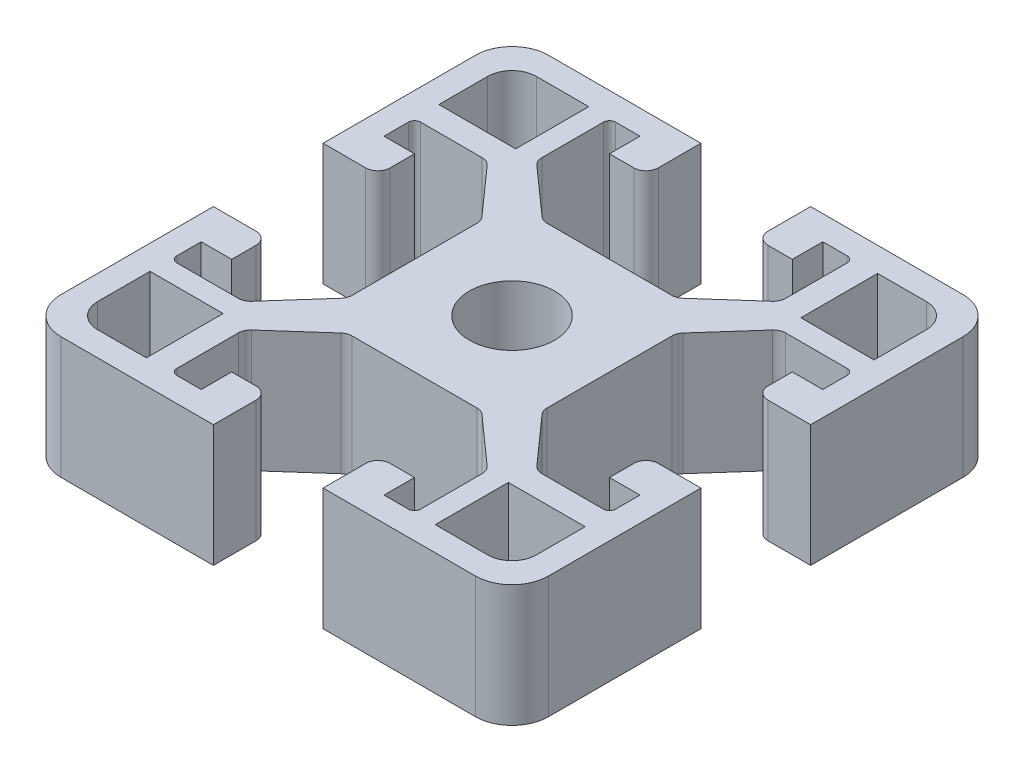
SolidWorks part; units mm, degrees
ref_plane "前视基准面" through (0, 0, 0) normal (0, 0, 1) x (1, 0, 0)
ref_plane "上视基准面" through (0, 0, 0) normal (0, 1, 0) x (1, 0, 0)
ref_plane "右视基准面" through (0, 0, 0) normal (1, 0, 0) x (0, 0, -1)
sketch "草图1" plane through (0, 0, 0) normal (0, 1, 0) x (1, 0, 0)
  line L0 (0, 32.6515) -> (0, -47.5) construction
  line L1 (11.7017, 9.6644) -> (8.2526, 5.7842)
  line L2 (-54.5455, 0) -> (57.7273, 0) construction
  line L3 (-17, 20) -> (-4.5, 20)
  line L4 (-20, 17) -> (-20, 4.5)
  line L5 (-17, -20) -> (-4.5, -20)
  line L6 (20, 17) -> (20, 4.5)
  line L7 (-9.6644, 11.7017) -> (-5.7842, 8.2526)
  line L8 (-10, 17.5) -> (-10, 12.4491)
  line L9 (-7.5, 18) -> (-9.5, 18)
  line L10 (-7.5, 15.5) -> (-7.5, 18)
  line L11 (-5.5, 15.5) -> (-7.5, 15.5)
  line L12 (-4.5, 20) -> (-4.5, 16.5)
  line L14 (17.5, 10) -> (12.4491, 10)
  line L15 (18, 7.5) -> (18, 9.5)
  line L16 (15.5, 7.5) -> (18, 7.5)
  line L17 (15.5, 5.5) -> (15.5, 7.5)
  line L18 (20, 4.5) -> (16.5, 4.5)
  line L20 (20, -4.5) -> (16.5, -4.5)
  line L21 (15.5, -5.5) -> (15.5, -7.5)
  line L22 (15.5, -7.5) -> (18, -7.5)
  line L23 (4.5, 20) -> (4.5, 16.5)
  line L24 (5.5, 15.5) -> (7.5, 15.5)
  line L25 (7.5, 15.5) -> (7.5, 18)
  line L26 (7.5, 18) -> (9.5, 18)
  line L27 (10, 17.5) -> (10, 12.4491)
  line L28 (9.6644, 11.7017) -> (5.7842, 8.2526)
  line L29 (5.1198, 8) -> (-5.1198, 8)
  line L30 (18, -7.5) -> (18, -9.5)
  line L31 (17.5, -10) -> (12.4491, -10)
  line L32 (11.7017, -9.6644) -> (8.2526, -5.7842)
  line L33 (8, -5.1198) -> (8, 5.1198)
  line L34 (9.6644, -11.7017) -> (5.7842, -8.2526)
  line L35 (10, -17.5) -> (10, -12.4491)
  line L36 (7.5, -18) -> (9.5, -18)
  line L37 (7.5, -15.5) -> (7.5, -18)
  line L38 (5.5, -15.5) -> (7.5, -15.5)
  line L39 (4.5, -20) -> (4.5, -16.5)
  line L41 (-4.5, -20) -> (-4.5, -16.5)
  line L42 (-5.5, -15.5) -> (-7.5, -15.5)
  line L43 (-7.5, -15.5) -> (-7.5, -18)
  line L44 (-7.5, -18) -> (-9.5, -18)
  line L45 (-10, -17.5) -> (-10, -12.4491)
  line L46 (-9.6644, -11.7017) -> (-5.7842, -8.2526)
  line L47 (-5.1198, -8) -> (5.1198, -8)
  line L48 (-11.7017, -9.6644) -> (-8.2526, -5.7842)
  line L49 (-17.5, -10) -> (-12.4491, -10)
  line L50 (-18, -7.5) -> (-18, -9.5)
  line L51 (-15.5, -7.5) -> (-18, -7.5)
  line L52 (-15.5, -5.5) -> (-15.5, -7.5)
  line L53 (-20, -4.5) -> (-16.5, -4.5)
  line L55 (-20, 4.5) -> (-16.5, 4.5)
  line L56 (-15.5, 5.5) -> (-15.5, 7.5)
  line L57 (-15.5, 7.5) -> (-18, 7.5)
  line L58 (-18, 7.5) -> (-18, 9.5)
  line L59 (-17.5, 10) -> (-12.4491, 10)
  line L60 (-11.7017, 9.6644) -> (-8.2526, 5.7842)
  line L61 (-8, 5.1198) -> (-8, -5.1198)
  line L62 (18, -12) -> (11.7017, -12)
  line L63 (12, 18) -> (12, 11.7017)
  line L64 (18, 16) -> (18, 11.7017)
  line L65 (12, 11.7017) -> (18, 11.7017)
  line L66 (16, -18) -> (11.7017, -18)
  line L67 (11.7017, -12) -> (11.7017, -18)
  line L68 (12, 18) -> (16, 18)
  line L69 (18, -12) -> (18, -16)
  line L70 (-12, -18) -> (-12, -11.7017)
  line L71 (-18, -16) -> (-18, -11.7017)
  line L72 (-12, -11.7017) -> (-18, -11.7017)
  line L73 (-12, -18) -> (-16, -18)
  line L74 (-18, 12) -> (-11.7017, 12)
  line L75 (-16, 18) -> (-11.7017, 18)
  line L76 (-11.7017, 12) -> (-11.7017, 18)
  line L77 (-18, 12) -> (-18, 16)
  line L79 (-20, -17) -> (-20, -4.5)
  line L81 (20, -17) -> (20, -4.5)
  line L82 (-19.1213, -19.1213) -> (19.1213, 19.1213) construction
  line L83 (-19.1213, 19.1213) -> (19.1213, -19.1213) construction
  line L84 (4.5, 20) -> (17, 20)
  line L90 (4.5, -20) -> (17, -20)
  arc A0 (5.5, 15.5) -> (4.5, 16.5) centre (5.5, 16.5) cw
  arc A1 (10, 17.5) -> (9.5, 18) centre (9.5, 17.5) ccw
  arc A2 (9.6644, 11.7017) -> (10, 12.4491) centre (9, 12.4491) ccw
  arc A3 (5.1198, 8) -> (5.7842, 8.2526) centre (5.1198, 9) ccw
  arc A4 (-5.1198, 8) -> (-5.7842, 8.2526) centre (-5.1198, 9) cw
  arc A5 (-9.6644, 11.7017) -> (-10, 12.4491) centre (-9, 12.4491) cw
  arc A6 (-10, 17.5) -> (-9.5, 18) centre (-9.5, 17.5) cw
  arc A7 (-5.5, 15.5) -> (-4.5, 16.5) centre (-5.5, 16.5) ccw
  arc A8 (15.5, -5.5) -> (16.5, -4.5) centre (16.5, -5.5) cw
  arc A9 (17.5, -10) -> (18, -9.5) centre (17.5, -9.5) ccw
  arc A10 (11.7017, -9.6644) -> (12.4491, -10) centre (12.4491, -9) ccw
  arc A11 (8, -5.1198) -> (8.2526, -5.7842) centre (9, -5.1198) ccw
  arc A12 (8, 5.1198) -> (8.2526, 5.7842) centre (9, 5.1198) cw
  arc A13 (11.7017, 9.6644) -> (12.4491, 10) centre (12.4491, 9) cw
  arc A14 (17.5, 10) -> (18, 9.5) centre (17.5, 9.5) cw
  arc A15 (15.5, 5.5) -> (16.5, 4.5) centre (16.5, 5.5) ccw
  arc A16 (-5.5, -15.5) -> (-4.5, -16.5) centre (-5.5, -16.5) cw
  arc A17 (-10, -17.5) -> (-9.5, -18) centre (-9.5, -17.5) ccw
  arc A18 (-9.6644, -11.7017) -> (-10, -12.4491) centre (-9, -12.4491) ccw
  arc A19 (-5.1198, -8) -> (-5.7842, -8.2526) centre (-5.1198, -9) ccw
  arc A20 (5.1198, -8) -> (5.7842, -8.2526) centre (5.1198, -9) cw
  arc A21 (9.6644, -11.7017) -> (10, -12.4491) centre (9, -12.4491) cw
  arc A22 (10, -17.5) -> (9.5, -18) centre (9.5, -17.5) cw
  arc A23 (5.5, -15.5) -> (4.5, -16.5) centre (5.5, -16.5) ccw
  arc A24 (-15.5, 5.5) -> (-16.5, 4.5) centre (-16.5, 5.5) cw
  arc A25 (-17.5, 10) -> (-18, 9.5) centre (-17.5, 9.5) ccw
  arc A26 (-11.7017, 9.6644) -> (-12.4491, 10) centre (-12.4491, 9) ccw
  arc A27 (-8, 5.1198) -> (-8.2526, 5.7842) centre (-9, 5.1198) ccw
  arc A28 (-8, -5.1198) -> (-8.2526, -5.7842) centre (-9, -5.1198) cw
  arc A29 (-11.7017, -9.6644) -> (-12.4491, -10) centre (-12.4491, -9) cw
  arc A30 (-17.5, -10) -> (-18, -9.5) centre (-17.5, -9.5) cw
  arc A31 (-15.5, -5.5) -> (-16.5, -4.5) centre (-16.5, -5.5) ccw
  circle A32 centre (0, 0) radius 3.5
  arc A33 (18, 16) -> (16, 18) centre (16, 16) ccw
  arc A34 (16, -18) -> (18, -16) centre (16, -16) ccw
  arc A35 (-18, -16) -> (-16, -18) centre (-16, -16) ccw
  arc A36 (-16, 18) -> (-18, 16) centre (-16, 16) ccw
  arc A37 (-20, 17) -> (-17, 20) centre (-17, 17) cw
  arc A38 (17, 20) -> (20, 17) centre (17, 17) cw
  arc A39 (17, -20) -> (20, -17) centre (17, -17) ccw
  arc A40 (-17, -20) -> (-20, -17) centre (-17, -17) cw
  point P36 (0, 8)
  point P67 (8, 0)
  point P98 (0, -8)
  point P129 (-8, 0)
  point P135 (0, 0)
  point P160 (0, 0)
  point P161 (0, 0)
  dimension "D3" = 1
  dimension "D4" = 0.5
  dimension "D5" = 1
  dimension "D6" = 1
  dimension "D7" = 2
  dimension "D8" = 3
  dimension "D9" = 3
  dimension "D10" = 3
  dimension "D11" = 3
extrude "凸台-拉伸1" add sketch "草图1" along normal blind 10
